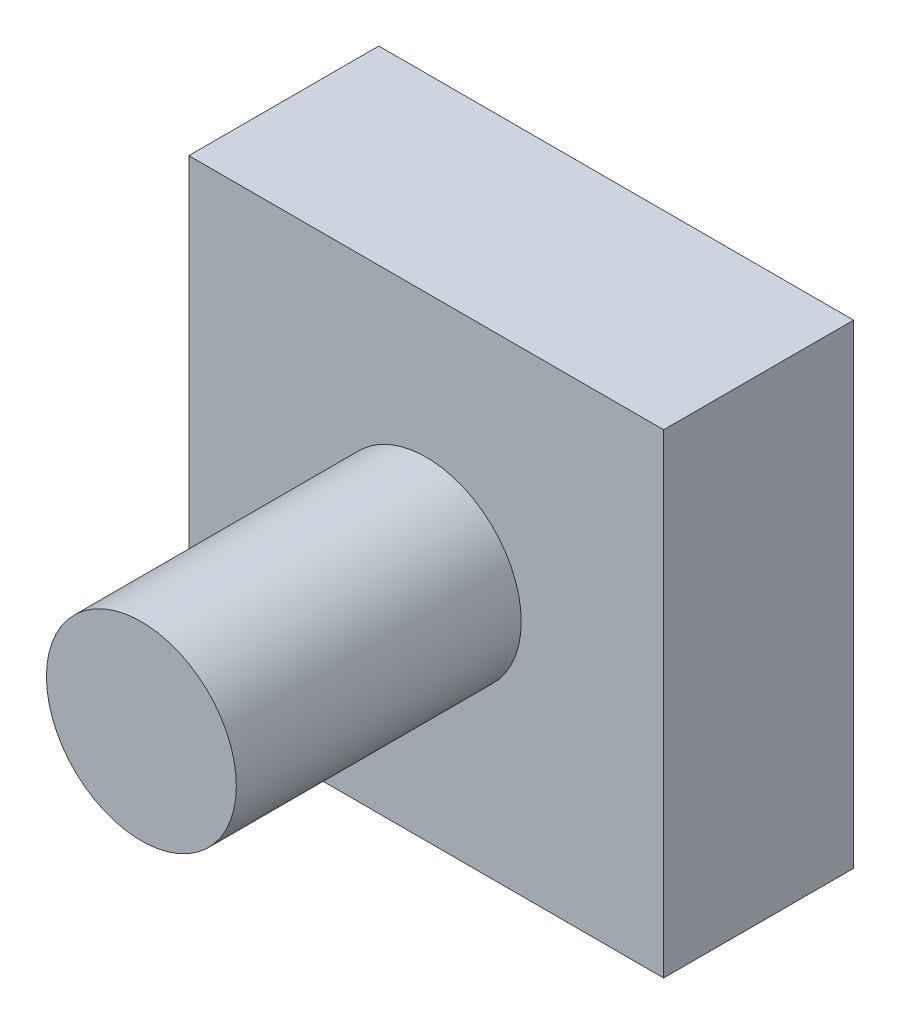
SolidWorks part; units mm, degrees
ref_plane "Front Plane" through (0, 0, 0) normal (0, 0, 1) x (1, 0, 0)
ref_plane "Top Plane" through (0, 0, 0) normal (0, 1, 0) x (1, 0, 0)
ref_plane "Right Plane" through (0, 0, 0) normal (1, 0, 0) x (0, 0, -1)
sketch "Sketch1" plane through (0, 0, 0) normal (0, 0, 1) x (1, 0, 0)
  line L1 (-25, 25) -> (25, 25)
  line L2 (-25, 25) -> (-25, -25)
  line L3 (-25, -25) -> (25, -25)
  line L4 (25, 25) -> (25, -25)
  line L5 (-25, 25) -> (25, -25) construction
  line L6 (-25, -25) -> (25, 25) construction
  point P0 (0, 0)
  dimension "D1" = 50
  dimension "D2" = 50
extrude "Boss-Extrude1" add sketch "Sketch1" against normal blind 20
sketch "Sketch2" plane through (0, 0, 0) normal (0, 0, 1) x (1, 0, 0)
  circle A0 centre (0, 0) radius 10
  point P4 (0, 0)
extrude "Boss-Extrude2" add sketch "Sketch2" along normal blind 30
